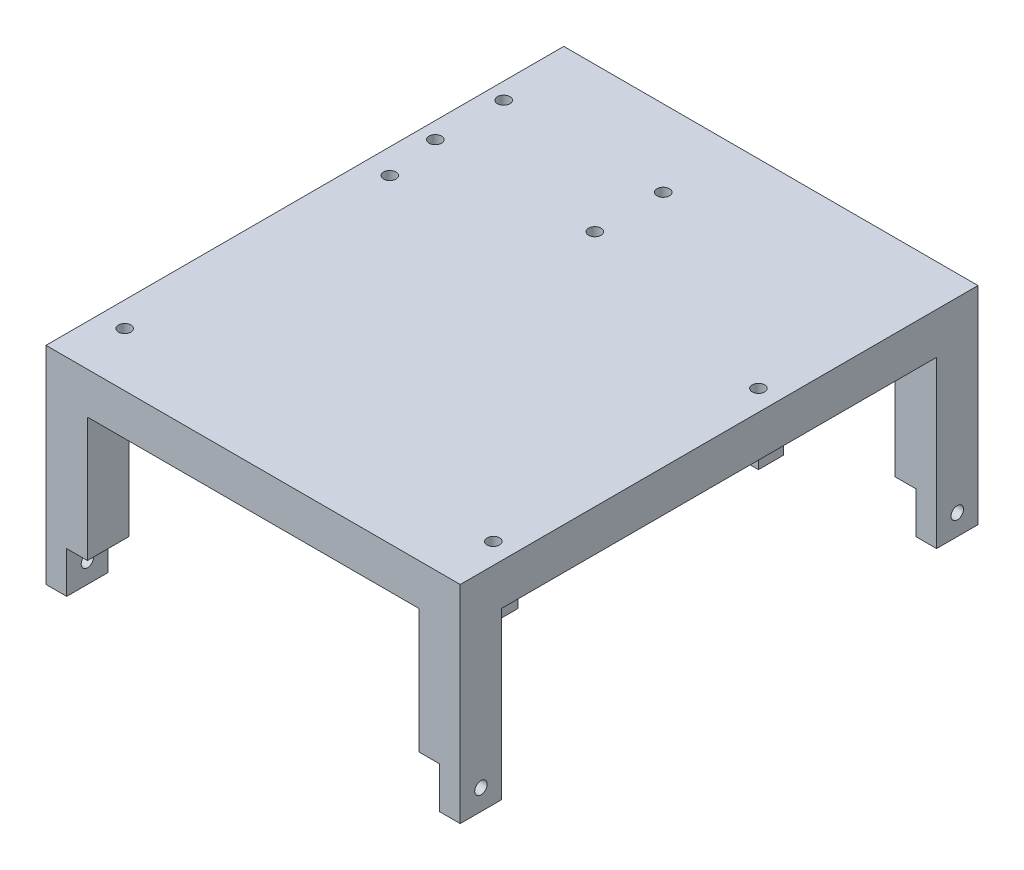
SolidWorks part; units mm, degrees
ref_plane "Front Plane" through (0, 0, 0) normal (0, 0, 1) x (1, 0, 0)
ref_plane "Top Plane" through (0, 0, 0) normal (0, 1, 0) x (1, 0, 0)
ref_plane "Right Plane" through (0, 0, 0) normal (1, 0, 0) x (0, 0, -1)
sketch "Sketch2" plane through (0, 0, 0) normal (0, 1, 0) x (1, 0, 0)
  line L1 (0, 0) -> (100, 0)
  line L2 (0, 0) -> (0, 80)
  line L3 (0, 80) -> (100, 80)
  line L4 (100, 0) -> (100, 80)
  dimension "D1" = 100
  dimension "D2" = 80
extrude "Boss-Extrude1" add sketch "Sketch2" along normal blind 10
sketch "Sketch3" plane through (0, 0, 0) normal (0, -1, 0) x (1, 0, 0)
  line L1 (100, 0) -> (90, 0)
  line L2 (100, 0) -> (100, -10)
  line L3 (100, -10) -> (90, -10)
  line L4 (90, 0) -> (90, -10)
  line L5 (0, 0) -> (10, 0)
  line L6 (0, 0) -> (0, -10)
  line L7 (0, -10) -> (10, -10)
  line L8 (10, 0) -> (10, -10)
  dimension "D1" = 10
  dimension "D2" = 10
extrude "Boss-Extrude2" add sketch "Sketch3" along normal blind 30
sketch "Sketch4" plane through (0, -30, 0) normal (0, -1, 0) x (1, 0, 0)
  line L0 (0, -10) -> (10, -10) construction
  line L1 (0, 0) -> (5, 0)
  line L2 (0, 0) -> (0, -10)
  line L3 (0, -10) -> (5, -10)
  line L4 (5, 0) -> (5, -10)
  line L5 (100, 0) -> (90, 0) construction
  line L6 (95, 0) -> (100, 0)
  line L7 (95, 0) -> (95, -10)
  line L8 (95, -10) -> (100, -10)
  line L9 (100, 0) -> (100, -10)
  line L10 (90, -10) -> (100, -10) construction
  line L11 (100, -10) -> (100, 0) construction
extrude "Boss-Extrude3" add sketch "Sketch4" along normal blind 10
sketch "Sketch5" plane through (0, 0, 0) normal (0, -1, 0) x (1, 0, 0)
  line L1 (3, -10) -> (9, -10)
  line L2 (3, -10) -> (3, -16)
  line L3 (3, -16) -> (9, -16)
  line L4 (9, -10) -> (9, -16)
  line L5 (98, -10) -> (92, -10)
  line L6 (98, -10) -> (98, -16)
  line L7 (98, -16) -> (92, -16)
  line L8 (92, -10) -> (92, -16)
  line L9 (98, -80) -> (92, -80)
  line L10 (98, -80) -> (98, -74)
  line L11 (98, -74) -> (92, -74)
  line L12 (92, -80) -> (92, -74)
  line L14 (3, -74) -> (9, -74)
  line L15 (3, -74) -> (3, -80)
  line L16 (3, -80) -> (9, -80)
  line L17 (9, -74) -> (9, -80)
  line L18 (100, -10) -> (100, -80) construction
  line L19 (100, -80) -> (0, -80) construction
  dimension "D1" = 6
  dimension "D2" = 70
  dimension "D3" = 95
  dimension "D4" = 2
extrude "Boss-Extrude4" add sketch "Sketch5" along normal blind 4
sketch "Sketch6" plane through (0, -4, 0) normal (0, -1, 0) x (1, 0, 0)
  line L0 (98, -16) -> (98, -10) construction
  line L1 (92, -16) -> (98, -16) construction
  line L2 (3, -74) -> (3, -80) construction
  line L3 (3, -80) -> (9, -80) construction
  circle A0 centre (6, -13) radius 1.5
  circle A1 centre (95, -13) radius 1.5
  circle A2 centre (95, -77) radius 1.5
  circle A3 centre (6, -77) radius 1.5
  point P8 (98, -13)
  dimension "D1" = 3
  dimension "D2" = 3
  dimension "D3" = 3
  dimension "D4" = 3
  dimension "D5" = 3
extrude "Cut-Extrude1" cut sketch "Sketch6" against normal through all
sketch "Sketch7" plane through (0, 0, -80) normal (0, 0, -1) x (-1, 0, 0)
  line L1 (0, 0) -> (-100, 0)
  line L2 (0, 0) -> (0, 10)
  line L3 (0, 10) -> (-100, 10)
  line L4 (-100, 0) -> (-100, 10)
extrude "Boss-Extrude5" add sketch "Sketch7" along normal blind 45
sketch "Sketch8" plane through (0, 0, 0) normal (0, -1, 0) x (1, 0, 0)
  line L1 (0, -125) -> (10, -125)
  line L2 (0, -125) -> (0, -115)
  line L3 (0, -115) -> (10, -115)
  line L4 (10, -125) -> (10, -115)
  line L5 (100, -125) -> (90, -125)
  line L6 (100, -125) -> (100, -115)
  line L7 (100, -115) -> (90, -115)
  line L8 (90, -125) -> (90, -115)
  dimension "D1" = 10
  dimension "D2" = 10
extrude "Boss-Extrude6" add sketch "Sketch8" along normal blind 30
sketch "Sketch9" plane through (0, -30, 0) normal (0, -1, 0) x (1, 0, 0)
  line L0 (0, -125) -> (10, -125) construction
  line L1 (0, -115) -> (5, -115)
  line L2 (0, -115) -> (0, -125)
  line L3 (0, -125) -> (5, -125)
  line L4 (5, -115) -> (5, -125)
  line L5 (90, -125) -> (100, -125) construction
  line L6 (100, -115) -> (95, -115)
  line L7 (100, -115) -> (100, -125)
  line L8 (100, -125) -> (95, -125)
  line L9 (95, -115) -> (95, -125)
extrude "Boss-Extrude7" add sketch "Sketch9" along normal blind 10
sketch "Sketch10" plane through (0, 0, 0) normal (-1, 0, 0) x (0, 0, 1)
  line L0 (0, -40) -> (-10, -40) construction
  line L1 (0, -30) -> (0, 0) construction
  line L2 (-125, -40) -> (-125, 10) construction
  circle A0 centre (-5, -35) radius 1.5
  circle A1 centre (-120, -35) radius 1.5
  dimension "D1" = 3
  dimension "D2" = 5
  dimension "D3" = 5
  dimension "D4" = 5
extrude "Cut-Extrude2" cut sketch "Sketch10" against normal through all
sketch "Sketch11" plane through (0, 0, 0) normal (0, -1, 0) x (1, 0, 0)
  line L0 (0, -115) -> (0, -10) construction
  line L1 (9, -80) -> (3, -80) construction
  circle A0 centre (4, -106.5) radius 1.5
  circle A1 centre (4, -90) radius 1.5
  circle A2 centre (42.5, -106.5) radius 1.5
  circle A3 centre (42.5, -90) radius 1.5
  dimension "D4" = 3
  dimension "D5" = 10
  dimension "D1" = 16.5
  dimension "D2" = 38.5
  dimension "D3" = 4
extrude "Cut-Extrude3" cut sketch "Sketch11" against normal up to surface (10 mm away) up to face at (6, 10, -78.5)
